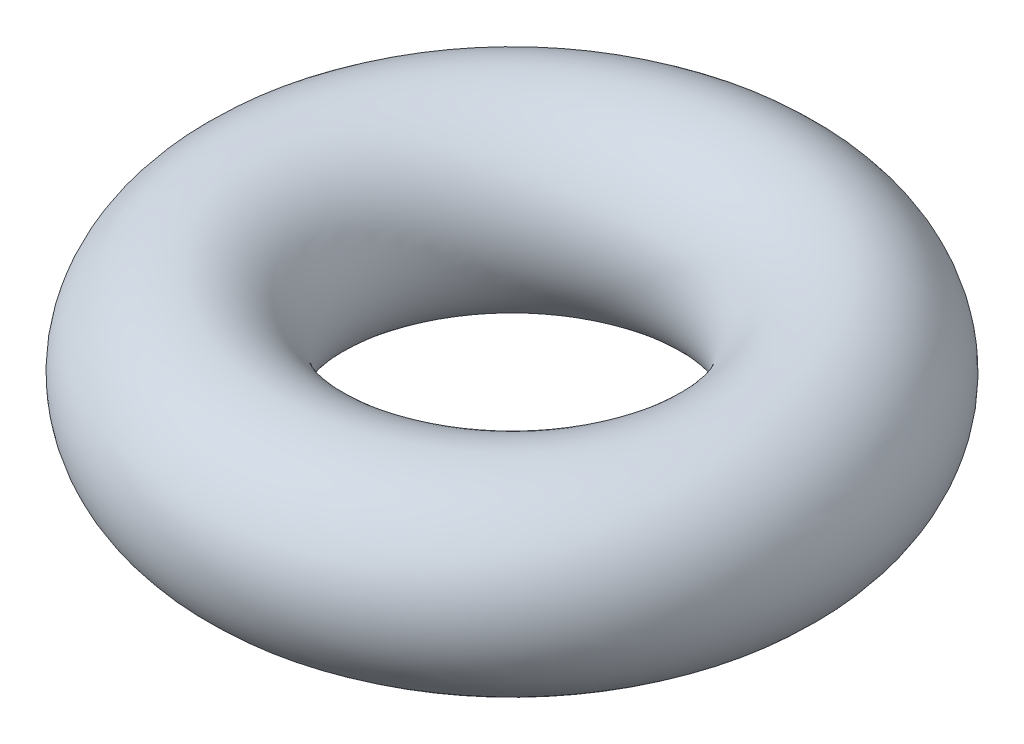
SolidWorks part; units mm, degrees
ref_plane "Front Plane" through (0, 0, 0) normal (0, 0, 1) x (1, 0, 0)
ref_plane "Top Plane" through (0, 0, 0) normal (0, 1, 0) x (1, 0, 0)
ref_plane "Right Plane" through (0, 0, 0) normal (1, 0, 0) x (0, 0, -1)
sketch "Sketch1" plane through (0, 0, 0) normal (0, 0, 1) x (1, 0, 0)
  line L0 (-63.5, 38.3827) -> (-63.5, -32.3399) construction
  circle A0 centre (0, 0) radius 25.4
  dimension "D1" = 50.8
  dimension "2.5" = 63.5
revolve "Revolve1" add sketch "Sketch1" angle 360 about L0
